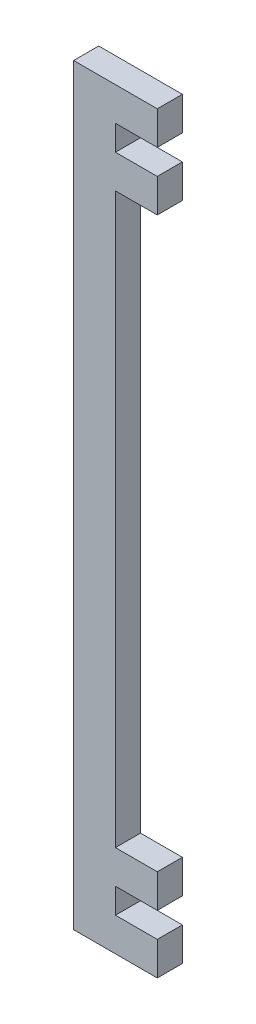
SolidWorks part; units mm, degrees
ref_plane "前视" through (0, 0, 0) normal (0, 0, 1) x (1, 0, 0)
ref_plane "上视" through (0, 0, 0) normal (0, 1, 0) x (1, 0, 0)
ref_plane "右视" through (0, 0, 0) normal (1, 0, 0) x (0, 0, -1)
sketch "草图1" plane through (0, 0, 0) normal (0, 0, 1) x (1, 0, 0)
  line L0 (-83.0739, 45) -> (141.0551, 45) construction
  line L1 (0, 0) -> (10, 0)
  line L2 (0, 0) -> (0, 90)
  line L3 (10, 79) -> (5, 79)
  line L4 (10, 83) -> (10, 79)
  line L5 (10, 0) -> (10, 4)
  line L6 (10, 4) -> (5, 4)
  line L7 (5, 4) -> (5, 7)
  line L8 (5, 7) -> (10, 7)
  line L9 (10, 7) -> (10, 11)
  line L10 (10, 11) -> (5, 11)
  line L11 (5, 11) -> (5, 79)
  line L12 (5, 83) -> (10, 83)
  line L13 (5, 86) -> (5, 83)
  line L14 (10, 86) -> (5, 86)
  line L15 (10, 90) -> (10, 86)
  line L16 (0, 90) -> (10, 90)
  point P2 (5, 45)
  point P21 (0, 45)
  dimension "D1" = 38
  dimension "D2" = 4
  dimension "D3" = 3
  dimension "D4" = 4
  dimension "D5" = 5
  dimension "D6" = 10
  dimension "D7" = 5
  dimension "D8" = 5
extrude "凸台-拉伸1" add sketch "草图1" along normal blind 3
